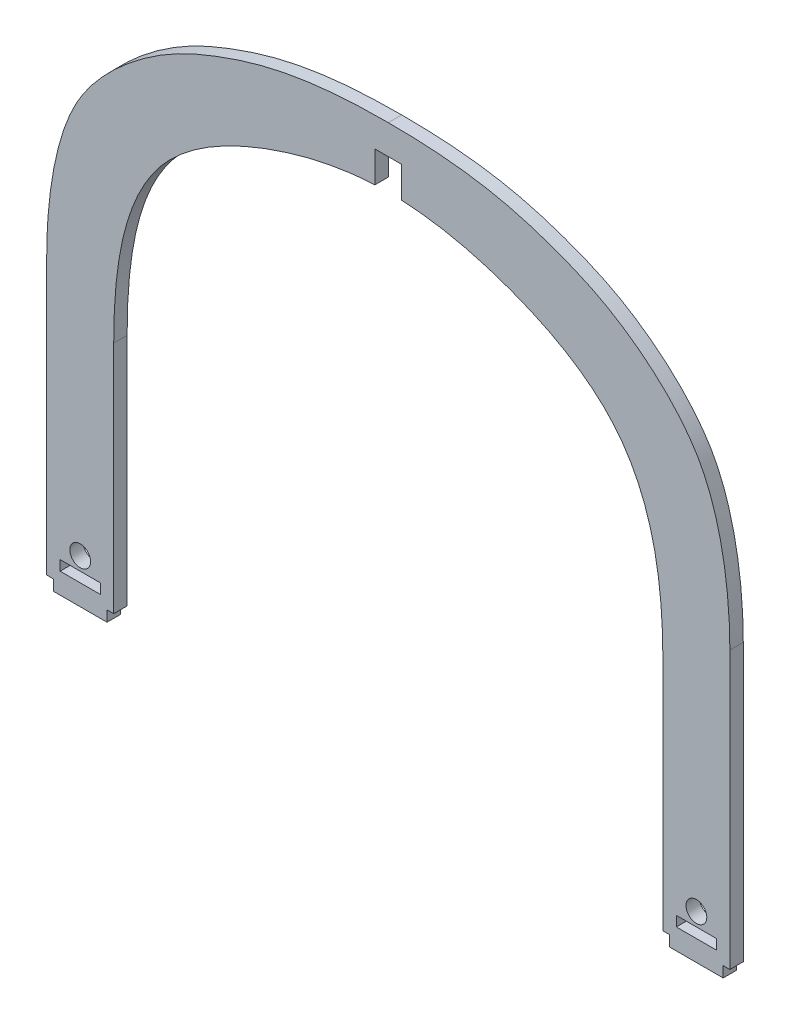
SolidWorks part; units mm, degrees
ref_plane "前视基准面" through (0, 0, 0) normal (0, 0, 1) x (1, 0, 0)
ref_plane "上视基准面" through (0, 0, 0) normal (0, 1, 0) x (1, 0, 0)
ref_plane "右视基准面" through (0, 0, 0) normal (1, 0, 0) x (0, 0, -1)
sketch "草图1" plane through (0, 0, 0) normal (0, 0, 1) x (1, 0, 0)
  line L0 (0, 0) -> (1, 0)
  line L1 (10, 0) -> (10, 35)
  line L2 (0, 0) -> (0, 41.3187)
  line L3 (10, 0) -> (92, 0) construction
  line L4 (51, 0) -> (51, 91.6216) construction
  line L5 (92, 35) -> (92, 0)
  line L6 (92, 0) -> (93, 0)
  line L7 (102, 0) -> (102, 41.3187)
  line L8 (93, -1.6) -> (101, -1.6)
  line L9 (101, -1.6) -> (101, 0)
  line L10 (93, -1.6) -> (93, 0)
  line L11 (9, -1.6) -> (9, 0)
  line L12 (9, -1.6) -> (1, -1.6)
  line L13 (1, -1.6) -> (1, 0)
  line L14 (101, 0) -> (102, 0)
  line L15 (9, 0) -> (10, 0)
  spline S0 degree 3 poles (0, 41.3187) (0, 48.3906) (1.3251, 58.8307) (8.6719, 69.8334) (16.3976, 76.0794) (30.7396, 82.0516) (39.3613, 84) (51, 84) knots 0 0 0 0 0.315307 0.38076 0.624111 0.689077 1 1 1 1
  spline S1 degree 3 poles (102, 41.3187) (102, 48.3906) (100.6749, 58.8307) (93.3281, 69.8334) (85.6024, 76.0794) (71.2604, 82.0516) (62.6387, 84) (51, 84) knots 0 0 0 0 0.315307 0.38076 0.624111 0.689077 1 1 1 1
  spline S2 degree 3 poles (92, 35) (92, 45.9589) (89.1979, 61.8504) (68.861, 72.6058) (56.8497, 75) (51, 75) knots 0 0 0 0 0.441101 0.721666 1 1 1 1
  spline S3 degree 3 poles (10, 35) (10, 45.9589) (12.8021, 61.8504) (33.139, 72.6058) (45.1503, 75) (51, 75) knots 0 0 0 0 0.441101 0.721666 1 1 1 1
  point P15 (97, -1.6)
  dimension "D1" = 10
  dimension "D2" = 35
  dimension "D3" = 82
  dimension "D4" = 8
  dimension "D5" = 1
  dimension "D6" = 1.6
  dimension "D7" = 9
  dimension "D8" = 40
extrude "保护罩主体" add sketch "草图1" along normal blind 2
sketch "下槽口" plane through (0, 0, 0) normal (0, 0, -1) x (-1, 0, 0)
  line L0 (-53, 73) -> (-49, 73)
  line L1 (-49, 73) -> (-49, 79.6)
  line L4 (-10, 35) -> (-92, 35) construction
  line L5 (-51, 35) -> (-51, 58.4038) construction
  line L6 (-49, 79.6) -> (-53, 79.6)
  line L7 (-53, 79.6) -> (-53, 73)
  dimension "D1" = 2
  dimension "D2" = 4
  dimension "D3" = 38
  dimension "D4" = 4.6
extrude "错孔_下" cut sketch "下槽口" against normal through all
sketch "安装孔" plane through (0, 0, 0) normal (0, 0, -1) x (-1, 0, 0)
  line L0 (-92, 0) -> (-93, 0) construction
  line L1 (-51, 86) -> (-51, -18.3042) construction
  line L2 (-92, 35) -> (-92, 0) construction
  circle A0 centre (-97, 5) radius 1.55
  circle A2 centre (-5, 5) radius 1.55
  dimension "D1" = 5
  dimension "D2" = 3.1
  dimension "D3" = 5
extrude "安装孔_" cut sketch "安装孔" against normal through all
sketch "草图4" plane through (0, 0, 0) normal (0, 0, -1) x (-1, 0, 0)
  line L0 (-100, 1.5) -> (-94, 1.5)
  line L1 (-94, 1.5) -> (-94, 3)
  line L2 (-94, 3) -> (-100, 3)
  line L8 (-100, 3) -> (-100, 1.5)
  line L9 (-101, 0) -> (-102, 0) construction
  line L11 (-93, 0) -> (-93, -1.6) construction
  line L12 (-92, 0) -> (-10, 0) construction
  line L13 (-51, 0) -> (-51, 26.9655) construction
  line L14 (-8, 1.5) -> (-8, 3)
  line L15 (-2, 1.5) -> (-8, 1.5)
  line L16 (-2, 3) -> (-2, 1.5)
  line L17 (-8, 3) -> (-2, 3)
  dimension "D1" = 6
  dimension "D2" = 1.5
  dimension "D3" = 1.5
  dimension "D4" = 1
extrude "安装压板过孔" cut sketch "草图4" against normal through all
